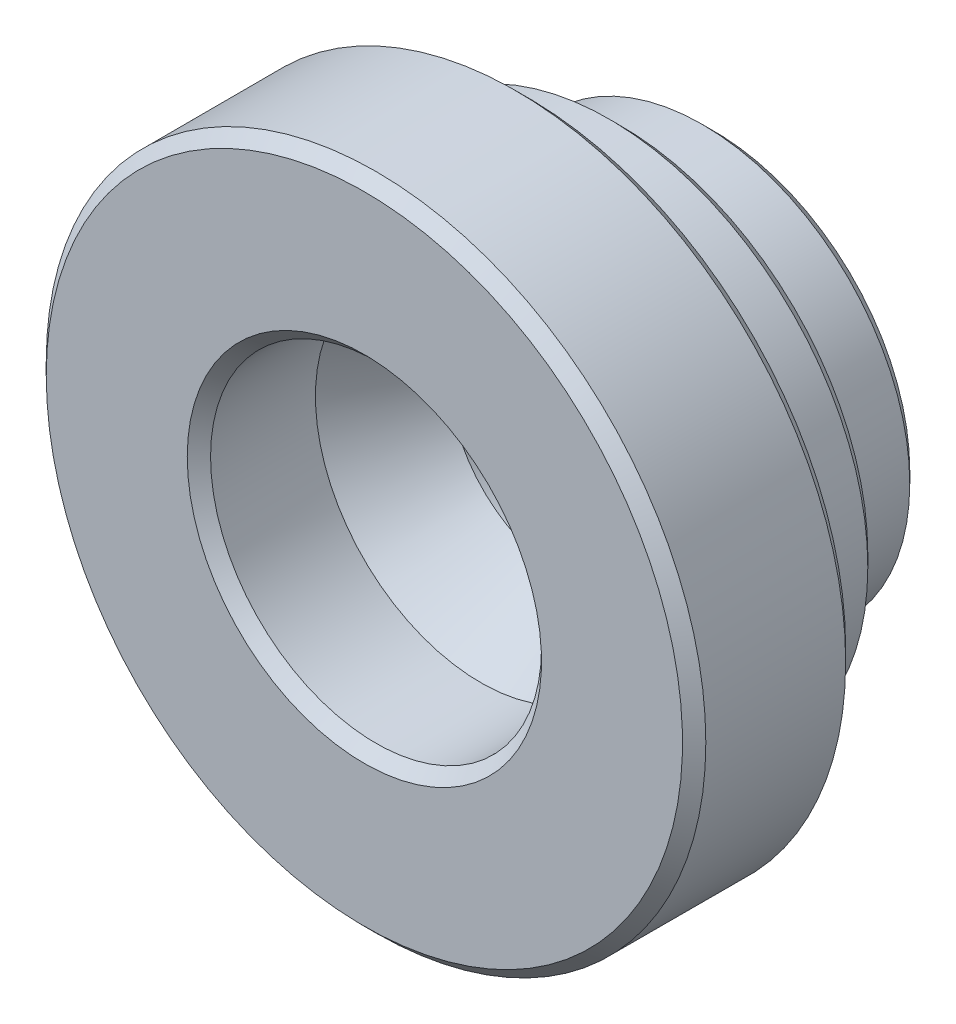
SolidWorks part; units mm, degrees
ref_plane "Front Plane" through (0, 0, 0) normal (0, 0, 1) x (1, 0, 0)
ref_plane "Top Plane" through (0, 0, 0) normal (0, 1, 0) x (1, 0, 0)
ref_plane "Right Plane" through (0, 0, 0) normal (1, 0, 0) x (0, 0, -1)
sketch "Sketch2" plane through (0, 0, 0) normal (1, 0, 0) x (0, 0, -1)
  line L0 (0, 0) -> (15, 0) construction
  line L1 (15, 8.9) -> (11, 8.9)
  line L2 (11, 8.9) -> (11, 11.1)
  line L3 (11, 11.1) -> (7, 11.1)
  line L4 (7, 11.1) -> (7, 14.15)
  line L5 (7, 14.15) -> (0, 14.15)
  line L6 (15, 8.9) -> (15, 5)
  line L7 (0, 14.15) -> (0, 7.1)
  line L8 (0, 7.1) -> (5, 7.1)
  line L10 (8.6373, 5) -> (15, 5)
  line L11 (5, 7.1) -> (8.6373, 5)
  dimension "D1" = 4
  dimension "D2" = 17.8
  dimension "D3" = 7
  dimension "D4" = 28.3
  dimension "D5" = 22.2
  dimension "D6" = 4
  dimension "D7" = 10
  dimension "D8" = 14.2
  dimension "D9" = 5
  dimension "D10" = 30
revolve "Revolve1" add sketch "Sketch2" angle 360 about L0
chamfer "Chamfer1" distance 0.5 angle 45 5 edges at (14.15, 0, -7) (11.1, 0, -11) (8.9, 0, -15) (7.1, 0, 0) (14.15, 0, 0)
